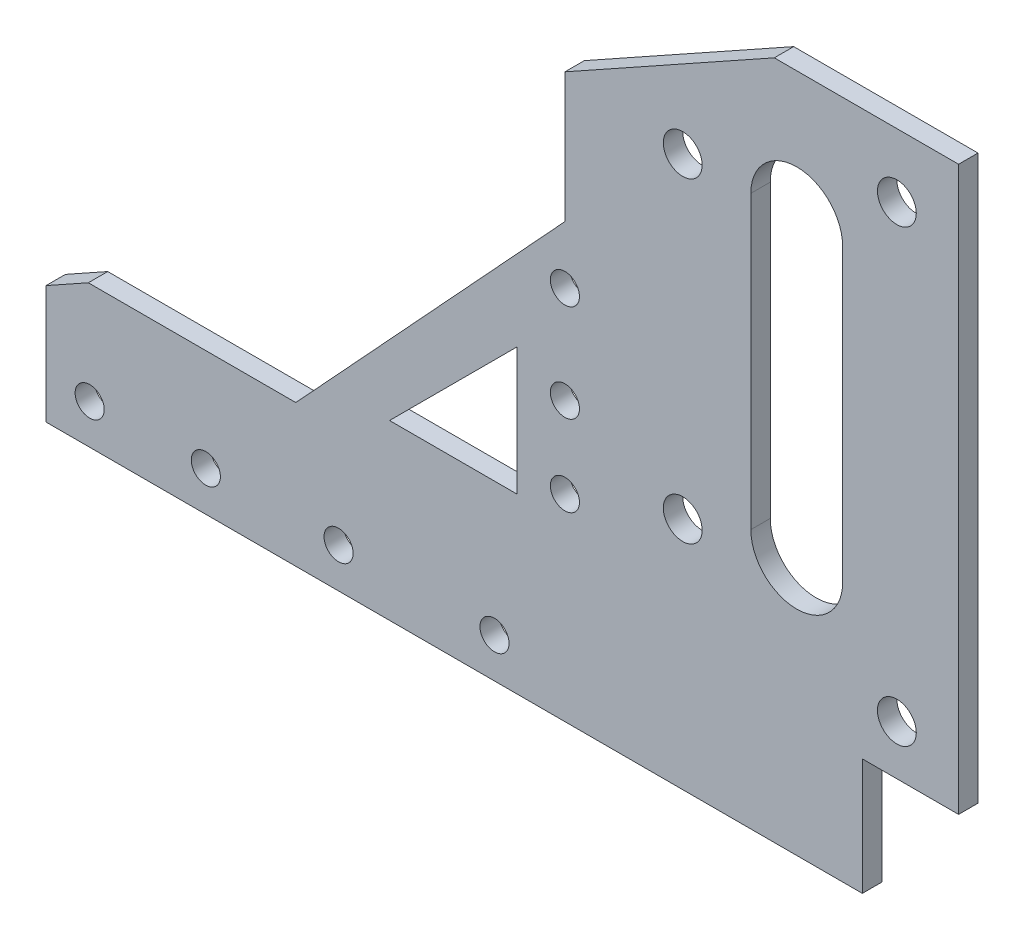
SolidWorks part; units mm, degrees
ref_plane "Front Plane" through (0, 0, 0) normal (0, 0, 1) x (1, 0, 0)
ref_plane "Top Plane" through (0, 0, 0) normal (0, 1, 0) x (1, 0, 0)
ref_plane "Right Plane" through (0, 0, 0) normal (1, 0, 0) x (0, 0, -1)
sketch "Sketch1" plane through (0, 0, 0) normal (0, 0, 1) x (1, 0, 0)
  line L0 (-98.0551, -17.8593) -> (322.3825, -17.8593)
  line L7 (322.3825, -17.8593) -> (322.3825, 42.1407)
  line L8 (322.3825, 42.1407) -> (371.9449, 42.1407)
  line L9 (371.9449, 42.1407) -> (371.9449, 332.1407)
  line L10 (277.025, 332.1407) -> (169.1871, 271.9751)
  line L11 (169.1871, 271.9751) -> (169.1871, 205.17)
  line L12 (169.1871, 205.17) -> (30.5872, 55.17)
  line L13 (30.5872, 55.17) -> (-76.2686, 55.17)
  line L14 (-76.2686, 55.17) -> (-98.0551, 43.0148)
  line L15 (-98.0551, 43.0148) -> (-98.0551, -17.8593)
  line L16 (277.025, 332.1407) -> (371.9449, 332.1407)
  line L17 (30.5872, 55.17) -> (169.1871, 55.17) construction
  line L18 (169.1871, 55.17) -> (169.1871, 205.17) construction
  line L20 (288.5916, 265.6711) -> (288.5916, 115.6711) construction
  line L21 (312.226, 265.6711) -> (312.226, 115.6711)
  line L22 (264.9573, 265.6711) -> (264.9573, 115.6711)
  line L23 (78.8749, 71.3065) -> (144.6208, 137.0524)
  line L24 (144.6208, 137.0524) -> (144.6208, 71.3065)
  line L25 (144.6208, 71.3065) -> (78.8749, 71.3065)
  arc A0 (312.226, 265.6711) -> (264.9573, 265.6711) centre (288.5916, 265.6711) ccw
  arc A1 (264.9573, 115.6711) -> (312.226, 115.6711) centre (288.5916, 115.6711) ccw
  circle A2 centre (-15.7522, 2.6498) radius 7.5
  circle A3 centre (-75.5568, 2.6498) radius 7.5
  circle A4 centre (52.6368, 2.6498) radius 7.5
  circle A5 centre (132.9259, 2.6498) radius 7.5
  circle A6 centre (169.1871, 83.664) radius 7.5
  circle A7 centre (169.1871, 125.3575) radius 7.5
  circle A8 centre (169.1871, 175.474) radius 7.5
  circle A9 centre (229.8703, 265.6711) radius 10
  circle A10 centre (229.8703, 102.8253) radius 10
  circle A11 centre (340.1596, 299.3232) radius 10
  circle A12 centre (340.1596, 67.6675) radius 10
  point P0 (141.77, 160.7339)
  point P19 (288.5916, 190.6711)
  point P44 (144.6208, 71.3065)
  dimension "D1" = 15
  dimension "D2" = 20
  dimension "D3" = 150
extrude "Boss-Extrude1" add sketch "Sketch1" along normal blind 10
